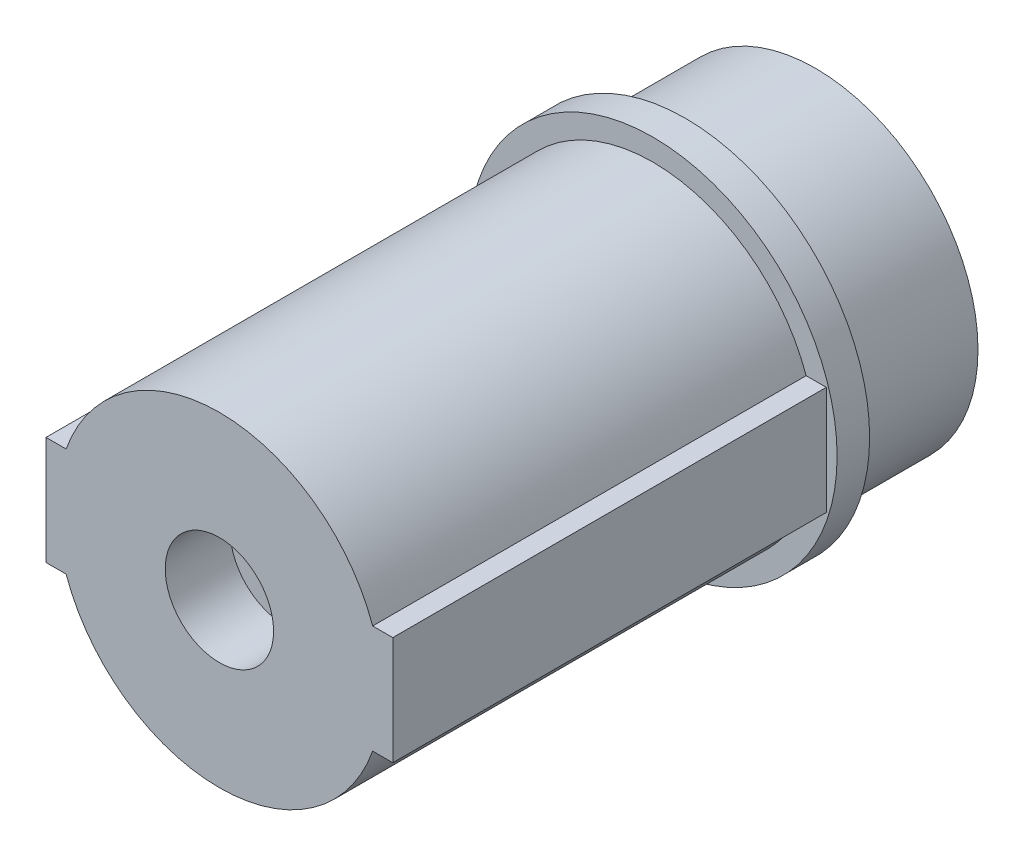
SolidWorks part; units mm, degrees
ref_plane "Front Plane" through (0, 0, 0) normal (0, 0, 1) x (1, 0, 0)
ref_plane "Top Plane" through (0, 0, 0) normal (0, 1, 0) x (1, 0, 0)
ref_plane "Right Plane" through (0, 0, 0) normal (1, 0, 0) x (0, 0, -1)
sketch "Sketch1" plane through (0, 0, 0) normal (0, 0, 1) x (1, 0, 0)
  circle A0 centre (0, 0) radius 15
  dimension "D1" = 30
extrude "Boss-Extrude1" add sketch "Sketch1" along normal blind 55
ref_plane "Plane1" through (0, 0, 0) normal (0, 0, -1) x (-1, 0, 0)
sketch "Sketch2" plane through (0, 0, 0) normal (0, 0, -1) x (-1, 0, 0)
  circle A0 centre (0, 0) radius 10
  dimension "D1" = 20
ref_plane "Plane3" through (0, 0, 55) normal (0, 0, 1) x (1, 0, 0)
extrude "Cut-Extrude7" cut sketch "Sketch2" against normal blind 46
ref_plane "Plane7" through (0, 0, 55) normal (0, 0, 1) x (1, 0, 0)
sketch "Sketch7" plane through (0, 0, 55) normal (0, 0, 1) x (1, 0, 0)
  circle A0 centre (0, 0) radius 5
extrude "Cut-Extrude8" cut sketch "Sketch7" against normal blind 6
ref_plane "Plane8" through (0, 0, 49) normal (0, 0, 1) x (1, 0, 0)
sketch "Sketch8" plane through (0, 0, 49) normal (0, 0, 1) x (1, 0, 0)
  circle A0 centre (0, 0) radius 2.25
extrude "Cut-Extrude9" cut sketch "Sketch8" against normal blind 3
ref_plane "Plane9" through (0, 0, 46) normal (0, 0, -1) x (-1, 0, 0)
sketch "Sketch9" plane through (0, 0, 46) normal (0, 0, -1) x (-1, 0, 0)
  line L1 (-9.6825, -2.5) -> (-6.5, -2.5)
  line L2 (-6.5, -2.5) -> (-6.5, -7.5993)
  line L4 (-9.6825, 2.5) -> (-6.5, 2.5)
  line L5 (-6.5, 2.5) -> (-6.5, 7.5993)
  line L7 (9.6825, -2.5) -> (6.5, -2.5)
  line L8 (6.5, -2.5) -> (6.5, -7.5993)
  line L9 (6.5, 2.5) -> (6.5, 7.5993)
  line L10 (9.6825, 2.5) -> (6.5, 2.5)
  circle A0 centre (0, 0) radius 10 construction
  circle A1 centre (0, 0) radius 10 construction
  arc A2 (-9.6825, -2.5) -> (-6.5, -7.5993) centre (0, 0) ccw
  arc A3 (-9.6825, 2.5) -> (-6.5, 7.5993) centre (0, 0) cw
  arc A4 (9.6825, -2.5) -> (6.5, -7.5993) centre (0, 0) cw
  arc A5 (9.6825, 2.5) -> (6.5, 7.5993) centre (0, 0) ccw
extrude "Boss-Extrude5" add sketch "Sketch9" along normal blind 6
sketch "Sketch10" plane through (0, 0, 55) normal (0, 0, 1) x (1, 0, 0)
  line L2 (-16, 5) -> (-16, -5)
  line L6 (-16, 5) -> (-14.1421, 5)
  line L8 (-14.1421, -5) -> (-16, -5)
  line L10 (0, 15) -> (0, -15)
  line L11 (16, 5) -> (16, -5)
  line L12 (14.1421, -5) -> (16, -5)
  line L13 (16, 5) -> (14.1421, 5)
  arc A0 (14.1421, 5) -> (14.1421, -5) centre (0, 0) cw
  circle A2 centre (0, 0) radius 15 construction
  arc A3 (-14.1421, 5) -> (-14.1421, -5) centre (0, 0) ccw
  dimension "D3" = 10
ref_plane "Plane10" through (0, 0, 15) normal (0, 0, 1) x (1, 0, 0)
sketch "Sketch11" plane through (0, 0, 15) normal (0, 0, 1) x (1, 0, 0)
  circle A0 centre (0, 0) radius 17
  circle A1 centre (0, 0) radius 15
extrude "Boss-Extrude6" add sketch "Sketch11" against normal blind 3 contours A0 A1
extrude "Boss-Extrude8" add sketch "Sketch10" against normal blind 40 contours L13 A0 L12 L11 | A3 L6 L2 L8
